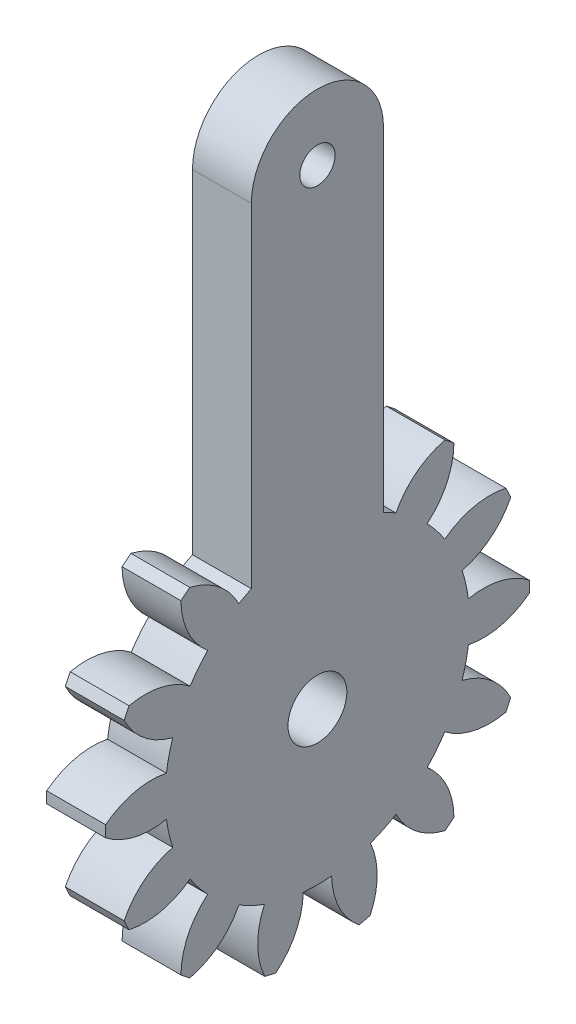
SolidWorks part; units mm, degrees
ref_plane "Plane1" through (0, 0, 0) normal (0, 0, 1) x (1, 0, 0)
ref_plane "Plane2" through (0, 0, 0) normal (0, 1, 0) x (1, 0, 0)
ref_plane "Plane3" through (0, 0, 0) normal (1, 0, 0) x (0, 0, -1)
other "Configuration Table"
sketch "HoldingSke" plane through (0, 0, 0) normal (0, 1, 0) x (1, 0, 0)
  line L0 (0, 0) -> (0.4312, -0.1075)
  line L1 (-15, 0) -> (100, 0) construction
  line L2 (0, 0) -> (-2.1039, 2.3779)
  line L3 (0, 0) -> (-11.863, 4.5341)
  line L4 (0, 0) -> (8.3795, 2.0892)
  line L5 (0, 0) -> (-46.8476, -17.4728)
  line L6 (0, 0) -> (-4.1448, -2.7965)
  line L7 (-2.1039, 2.3779) -> (8.6586, 51.2059)
  line L8 (-76.2, 54.61) -> (-75.3, 54.61)
  line L9 (-71.009, 38.7566) -> (-53.1078, 45.2721)
  line L10 (-76.2, 71.12) -> (104.1128, 71.12)
  line L11 (0, 0) -> (-5, 0)
  line L12 (-76.2, 101.6) -> (-76.123, 101.6)
  line L13 (24.9733, 27.94) -> (52.9518, 28.4284)
  line L14 (24.9733, 27.94) -> (24.9743, 27.94)
  line L15 (24.9733, 27.94) -> (100.4006, 29.5858)
  line L16 (-63.627, -2.25) -> (-12.827, -2.25)
  circle A0 centre (0, 0) radius 2.5
  circle A1 centre (0, 0) radius 12.9365
  circle A2 centre (0, 0) radius 37.5
  circle A3 centre (0, 0) radius 2.5
  dimension "MHD" = 25.873
  dimension "Hub_dia" = 75
  dimension "Bore" = 5
  dimension "MBD" = 5
  dimension "Num_teeth" = 14
  dimension "Pitch" = 0.4444
  dimension "Overall_len" = 50
  dimension "Show_teeth" = 14
  dimension "Thickness" = 5
  dimension "OAL" = 50.0001
  dimension "T_dim" = 0.9
  dimension "Ap" = 20
  dimension "H" = 19.05
  dimension "Pitch_radius" = 180.3128
  dimension "Width" = 5
  dimension "Backlash" = 0.077
  dimension "Addendum_fac" = 1
  dimension "Dedendum_fac" = 1.25
  dimension "Clearance_fac" = 0.25
  dimension "Dedendum_add" = 0.001
  dimension "Module" = 2.25
sketch "BasProSke" plane through (0, 0, 0) normal (0, 1, 0) x (1, 0, 0)
  line L0 (-10, 0) -> (60, 0) construction
  line L1 (0, 0) -> (0, 18)
  line L2 (0, 0) -> (5, 0)
  line L3 (5, 0) -> (5, 18)
  line L4 (5, 18) -> (0, 18)
  dimension "Thickness" = 5
  dimension "Diameter" = 36
revolve "Base-Revolve" add sketch "BasProSke" angle 360 about L0
sketch "TooCutSke" plane through (0, 0, 0) normal (1, 0, 0) x (0, 0, -1)
  line L1 (0, 0) -> (0, 107) construction
  line L2 (0, 0) -> (-1.8981, 15.6352) construction
  line L3 (0, 0) -> (-6.9718, 30.5456) construction
  line L4 (-1.8981, 15.6352) -> (-3.4859, 15.2728) construction
  arc A0 (1.2037, 12.8804) -> (-1.2037, 12.8804) centre (0, 0) ccw
  arc A1 (3.5588, 17.6706) -> (-3.5588, 17.6706) centre (0, 0) ccw
  circle A2 centre (0, 0) radius 15.75 construction
  circle A3 centre (0, 0) radius 14.8002 construction
  arc A4 (-1.2037, 12.8804) -> (-3.5588, 17.6706) centre (-7.5025, 12.7576) ccw
  arc A5 (3.5588, 17.6706) -> (1.2037, 12.8804) centre (7.5025, 12.7576) ccw
  dimension "Root_dia" = 25.873
  dimension "Overcut_dia" = 36.0508
  dimension "Pitch_dia" = 31.5
  dimension "Base_dia" = 29.6003
  dimension "Flank_rad" = 6.3
  dimension "Half_ang" = 12.857
  dimension "Half_CT" = 1.6287
extrude "ToothCut" cut sketch "TooCutSke" along normal through all
fillet "Breaks" [suppressed] radius 0.045
fillet "RootFillets" [suppressed] radius 0.5635
pattern_circular "TeethCuts" count 14 every 25.714 about axis through (-10, 0, 0) along (1, 0, 0) of "ToothCut", "RootFillets", "Breaks"
sketch "HubNeaOneSke" plane through (0, 0, 0) normal (-1, 0, 0) x (0, 0, 1)
  circle A0 centre (0, 0) radius 12.9365
  dimension "Diameter" = 25.873
extrude "HubNearOne" [suppressed] add sketch "HubNeaOneSke" along normal blind 45.0001
sketch "HubNeaBotSke" plane through (0, 0, 0) normal (-1, 0, 0) x (0, 0, 1)
  circle A0 centre (0, 0) radius 12.9365
  dimension "Diameter" = 25.873
extrude "HubNearBoth" [suppressed] add sketch "HubNeaBotSke" along normal blind 22.5
ref_plane "FarPln" through (5, 0, 0) normal (1, 0, 0) x (0, 0, -1)
sketch "HubFarSke" plane through (5, 0, 0) normal (1, 0, 0) x (0, 0, -1)
  circle A0 centre (0, 0) radius 12.9365
  dimension "Diameter" = 25.873
extrude "HubFar" [suppressed] add sketch "HubFarSke" along normal blind 22.5
sketch "BorSke" plane through (0, 0, 0) normal (1, 0, 0) x (0, 0, -1)
  circle A0 centre (0, 0) radius 2.5
  dimension "Diameter" = 5
extrude "Bore" cut sketch "BorSke" along normal mid plane 100.0001
sketch "KeySke" plane through (0, 0, 0) normal (1, 0, 0) x (0, 0, -1)
  line L0 (-1, 0) -> (-1, 3.4)
  line L1 (-1, 3.4) -> (1, 3.4)
  line L2 (1, 3.4) -> (1, 0)
  line L3 (0, 0) -> (0, 34) construction
  line L4 (-1, 0) -> (1, 0)
  dimension "Offset" = 3.4
  dimension "Width" = 2
extrude "Keyway" [suppressed] cut sketch "KeySke" along normal mid plane 100.0001
pattern_circular "Keyway2" [suppressed] count 2 every 90 about axis through (-10, 0, 0) along (1, 0, 0)
sketch "Esquisse1" plane through (5, 0, 0) normal (1, 0, 0) x (0, 0, -1)
  line L0 (0, 0) -> (0, 40) construction
  line L1 (-5.6129, 11.6554) -> (-5.6129, 40)
  line L2 (5.6129, 11.6554) -> (5.6129, 40)
  arc A0 (-4.5041, 12.1271) -> (-6.6731, 11.0826) centre (0, 0) ccw construction
  arc A1 (-5.6129, 40) -> (5.6129, 40) centre (0, 40) cw
  circle A2 centre (0, 40) radius 1.5
  arc A3 (-5.6129, 11.6554) -> (5.6129, 11.6554) centre (0, 0) cw
  dimension "D2" = 3
  dimension "D1" = 40
extrude "Boss.-Extru.1" add sketch "Esquisse1" against normal blind 5
equation "' \"Module@HoldingSke\" = 6.35"
equation "' \"Num_teeth@HoldingSke\" = 12"
equation "' \"Ap@HoldingSke\" =  20"
equation "' \"Ap@HoldingSke\" = 20"
equation "' \"Width@HoldingSke\" = 0.5 * 25.4"
equation "' \"Hub_dia@HoldingSke\"= 1 * 25.4"
equation "' \"Hub_dia@HoldingSke\" = 1 * 25.4"
equation "' \"Overall_len@HoldingSke\" = 1.0 * 25.4"
equation "' \"Bore@HoldingSke\" = 0.75 * 25.4"
equation "' \"T_dim@HoldingSke\" = 0.1 * 25.4"
equation "' \"Width@KeySke\" = 0.25 * 25.4"
equation "' \"Show_teeth@HoldingSke\" = 13"
equation "' \"Backlash@HoldingSke\" = 0.009 * 25.4"
equation "' \"Addendum_fac@HoldingSke\" = 1.0"
equation "' \"Dedendum_fac@HoldingSke\" = 1.25"
equation "' \"Dedendum_add@HoldingSke\" = 0.00005 * 25.4"
equation "' \"Clearance_fac@HoldingSke\" = 0.25"
equation "\"Pitch@HoldingSke\" = 1 / \"Module@HoldingSke\""
equation "\"Overcut_dia@TooCutSke\" = (\"Num_teeth@HoldingSke\" + 2 * \"Addendum_fac@HoldingSke\") / \"Pitch@HoldingSke\" + 0.002 * 25.4"
equation "\"Pitch_dia@TooCutSke\" = \"Num_teeth@HoldingSke\" / \"Pitch@HoldingSke\""
equation "\"Base_dia@TooCutSke\" = \"Num_teeth@HoldingSke\" / \"Pitch@HoldingSke\" * cos((\"Ap@HoldingSke\"  * 3.14159265 / 180))"
equation "\"Root_dia@TooCutSke\" = (\"Num_teeth@HoldingSke\" + 2) / \"Pitch@HoldingSke\" - 2 * (\"Addendum_fac@HoldingSke\" + \"Dedendum_fac@HoldingSke\") / \"Pitch@HoldingSke\" - \"Dedendum_add@HoldingSke\" * 2"
equation "\"Half_ang@TooCutSke\" = 180 / \"Num_teeth@HoldingSke\""
equation "\"Half_CT@TooCutSke\" = \"Num_teeth@HoldingSke\" / \"Pitch@HoldingSke\" * sin((3.14159265 / 2 / \"Num_teeth@HoldingSke\")) / 2 - 7 * \"Backlash@HoldingSke\" / 4"
equation "\"Flank_rad@TooCutSke\" = \"Num_teeth@HoldingSke\" / \"Pitch@HoldingSke\" / 5"
equation "\"Radius@RootFillets\" = \"Clearance_fac@HoldingSke\" / \"Pitch@HoldingSke\" + \"Dedendum_add@HoldingSke\""
equation "\"Break_rad@Breaks\" = 0.02 / \"Pitch@HoldingSke\""
equation "\"Thickness@HoldingSke\" = \"Width@HoldingSke\""
equation "\"OAL@HoldingSke\" = \"Thickness@HoldingSke\""
equation "\"MHD@HoldingSke\" = (\"Num_teeth@HoldingSke\" + 2) / \"Pitch@HoldingSke\" - 2 * (\"Addendum_fac@HoldingSke\" + \"Dedendum_fac@HoldingSke\")  / \"Pitch@HoldingSke\" - \"Dedendum_add@HoldingSke\" * 2"
equation "\"MBD@HoldingSke\" = (\"Num_teeth@HoldingSke\" + 2) / \"Pitch@HoldingSke\" - 2 * (\"Addendum_fac@HoldingSke\" + \"Dedendum_fac@HoldingSke\")  / \"Pitch@HoldingSke\" - \"Dedendum_add@HoldingSke\" * 2 - 0.002 * 25.4"
equation "\"MHD@HoldingSke\" = ((sgn( \"MHD@HoldingSke\" - \"Hub_dia@HoldingSke\" )-1)*( \"MHD@HoldingSke\" - \"Hub_dia@HoldingSke\" ))/-2+ \"Hub_dia@HoldingSke\""
equation "\"MBD@HoldingSke\" = ((sgn( \"MBD@HoldingSke\" - \"Bore@HoldingSke\" )-1)*( \"MBD@HoldingSke\" - \"Bore@HoldingSke\" ))/-2+ \"Bore@HoldingSke\""
equation "\"OAL@HoldingSke\" = ((sgn( \"OAL@HoldingSke\" - \"Overall_len@HoldingSke\" )+1)*( \"OAL@HoldingSke\" - \"Overall_len@HoldingSke\" ))/2 + \"Overall_len@HoldingSke\" + 0.000002 * 25.4"
equation "\"Num_teeth@TeethCuts\" = int( \"Show_teeth@HoldingSke\" ) + 1"
equation "\"Num_teeth@TeethCuts\" = ((sgn( \"Num_teeth@TeethCuts\" - \"Num_teeth@HoldingSke\" )-1)*( \"Num_teeth@TeethCuts\" - \"Num_teeth@HoldingSke\" ))/-2+ \"Num_teeth@HoldingSke\""
equation "\"Num_teeth@TeethCuts\" = ((sgn( \"Num_teeth@TeethCuts\" - 2.0)+1)*( \"Num_teeth@TeethCuts\" - 2.0))/2 +2.0"
equation "\"Angle@TeethCuts\" = 360.0 / \"Num_teeth@HoldingSke\""
equation "\"Diameter@BasProSke\" = (\"Num_teeth@HoldingSke\" + 2 * \"Addendum_fac@HoldingSke\") / \"Pitch@HoldingSke\""
equation "\"Thickness@BasProSke\"  = \"Thickness@HoldingSke\""
equation "' \"Fillet_rad@BasProSke\" =  \"Thickness@HoldingSke\" * 0.05"
equation "' \"Fillet_rad@BasProSke\" = \"Thickness@HoldingSke\" * 0.05"
equation "\"MHD@HoldingSke\" = ((sgn( \"MHD@HoldingSke\" - \"Root_dia@TooCutSke\" )-1)*( \"MHD@HoldingSke\" - \"Root_dia@TooCutSke\" ))/-2+ \"Root_dia@TooCutSke\""
equation "\"Diameter@HubNeaOneSke\" = \"MHD@HoldingSke\""
equation "\"Length@HubNearOne\" = \"OAL@HoldingSke\" - \"Thickness@BasProSke\""
equation "\"Diameter@HubNeaBotSke\" = \"MHD@HoldingSke\""
equation "\"Length@HubNearBoth\" = ( \"OAL@HoldingSke\" - \"Thickness@BasProSke\" ) / 2.0"
equation "\"Thickness@FarPln\" = \"Thickness@BasProSke\""
equation "\"Diameter@HubFarSke\" = \"MHD@HoldingSke\""
equation "\"Length@HubFar\" = ( \"OAL@HoldingSke\" - \"Thickness@BasProSke\" ) / 2.0"
equation "\"Diameter@BorSke\" = \"MBD@HoldingSke\""
equation "\"D1@Bore\" = \"OAL@HoldingSke\" * 2.0"
equation "\"D1@Keyway\" = \"OAL@HoldingSke\" * 2.0"
equation "\"Offset@KeySke\" = \"T_dim@HoldingSke\" + \"MBD@HoldingSke\" / 2.0"
